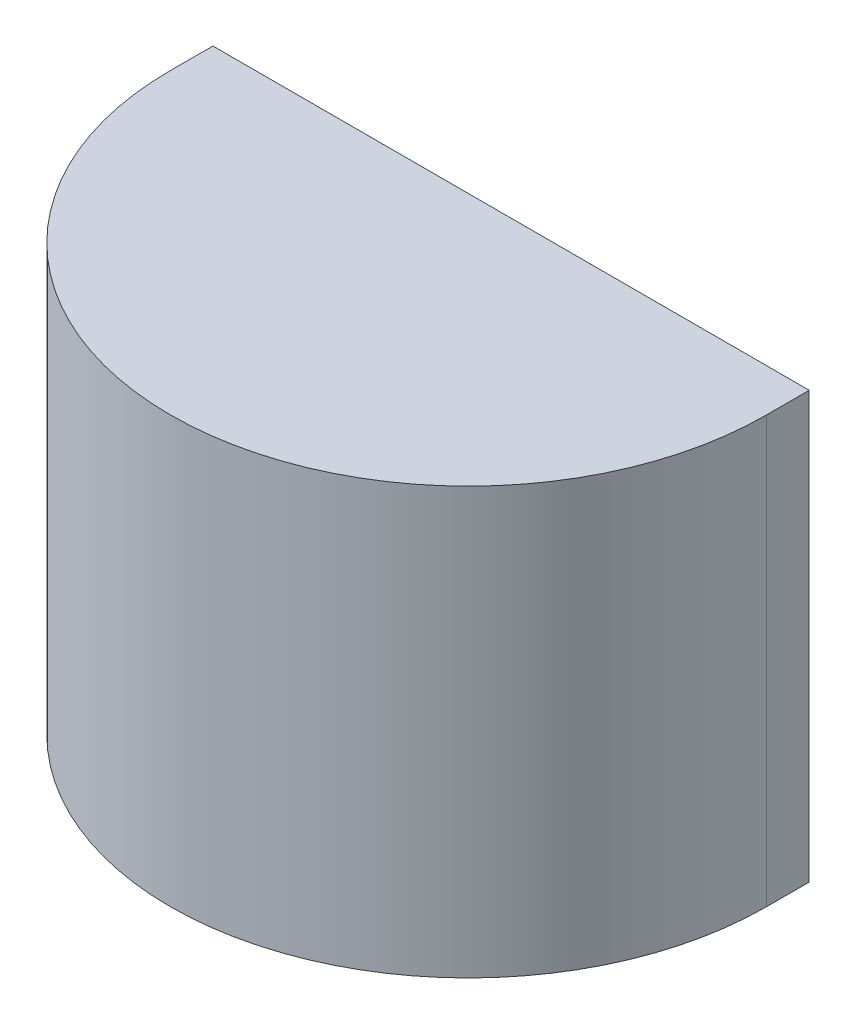
SolidWorks part; units mm, degrees
ref_plane "Front Plane" through (0, 0, 0) normal (0, 0, 1) x (1, 0, 0)
ref_plane "Top Plane" through (0, 0, 0) normal (0, 1, 0) x (1, 0, 0)
ref_plane "Right Plane" through (0, 0, 0) normal (1, 0, 0) x (0, 0, -1)
sketch "Sketch1" plane through (0, 0, 0) normal (0, 0, 1) x (1, 0, 0)
  line L0 (-31.75, 0) -> (31.75, 0) construction
  line L1 (-44.45, -12.7) -> (44.45, -12.7)
  line L2 (-44.45, -12.7) -> (-44.45, 12.7)
  line L3 (-44.45, 12.7) -> (44.45, 12.7)
  line L4 (44.45, -12.7) -> (44.45, 12.7)
  line L5 (-44.45, -12.7) -> (44.45, 12.7) construction
  line L6 (-44.45, 12.7) -> (44.45, -12.7) construction
  circle A0 centre (-31.75, 0) radius 4.3561
  circle A1 centre (31.75, 0) radius 4.3561
  point P0 (0, 0)
  point P8 (0, 0)
  dimension "D4" = 8.7122
  dimension "D1" = 25.4
  dimension "D2" = 88.9
  dimension "D3" = 63.5
extrude "Boss-Extrude1" add sketch "Sketch1" along normal blind 6.35
sketch "Sketch2" plane through (0, 12.7, 0) normal (0, 1, 0) x (1, 0, 0)
  line L1 (-44.45, -6.35) -> (44.45, -6.35)
  line L2 (-44.45, -6.35) -> (-44.45, 0)
  line L3 (-44.45, 0) -> (44.45, 0)
  line L4 (44.45, -6.35) -> (44.45, 0)
  arc A0 (-44.45, -6.35) -> (44.45, -6.35) centre (0, -6.35) ccw
  line M5 (44.45, 0) -> (-44.45, 0)
  line M6 (-44.45, 0) -> (-44.45, -6.35)
  line M7 (-44.45, -6.35) -> (44.45, -6.35)
  line M8 (44.45, -6.35) -> (44.45, 0)
extrude "Boss-Extrude2" add sketch "Sketch2" along normal blind 6.35 contours M8 M5 M6 M7 | A0 M7
sketch "Sketch3" plane through (0, 19.05, 0) normal (0, 1, 0) x (1, 0, 0)
  line L0 (38.1, -6.35) -> (38.1, -6.35)
  line L2 (-38.1, -6.35) -> (-38.1, -6.35)
  line L3 (44.45, -6.35) -> (44.45, 0)
  line L4 (44.45, 0) -> (-44.45, 0)
  line L5 (-44.45, 0) -> (-44.45, -6.35)
  line L6 (44.45, -6.35) -> (44.45, 0)
  line L7 (44.45, 0) -> (-44.45, 0)
  line L8 (-44.45, 0) -> (-44.45, -6.35)
  line L11 (-38.1, -6.35) -> (-38.1, 0)
  line L12 (-38.1, 0) -> (38.1, 0)
  line L13 (38.1, -6.35) -> (38.1, 0)
  line L14 (38.1, -6.35) -> (-38.1, -6.35) construction
  arc A0 (-38.1, -6.35) -> (38.1, -6.35) centre (0, -6.35) ccw
  arc A1 (-44.45, -6.35) -> (44.45, -6.35) centre (0, -6.35) ccw
  arc A2 (-44.45, -6.35) -> (44.45, -6.35) centre (0, -6.35) ccw
  line M5 (44.45, -6.35) -> (44.45, 0)
  line M6 (44.45, 0) -> (-44.45, 0)
  line M7 (-44.45, 0) -> (-44.45, -6.35)
  arc M8 (-44.45, -6.35) -> (44.45, -6.35) centre (0, -6.35) ccw
  dimension "D1" = 0
  dimension "D2" = 6.35
extrude "Boss-Extrude3" add sketch "Sketch3" against normal blind 63.5 contours A0 L11 L7 L13 M7 M8 M5 M6
